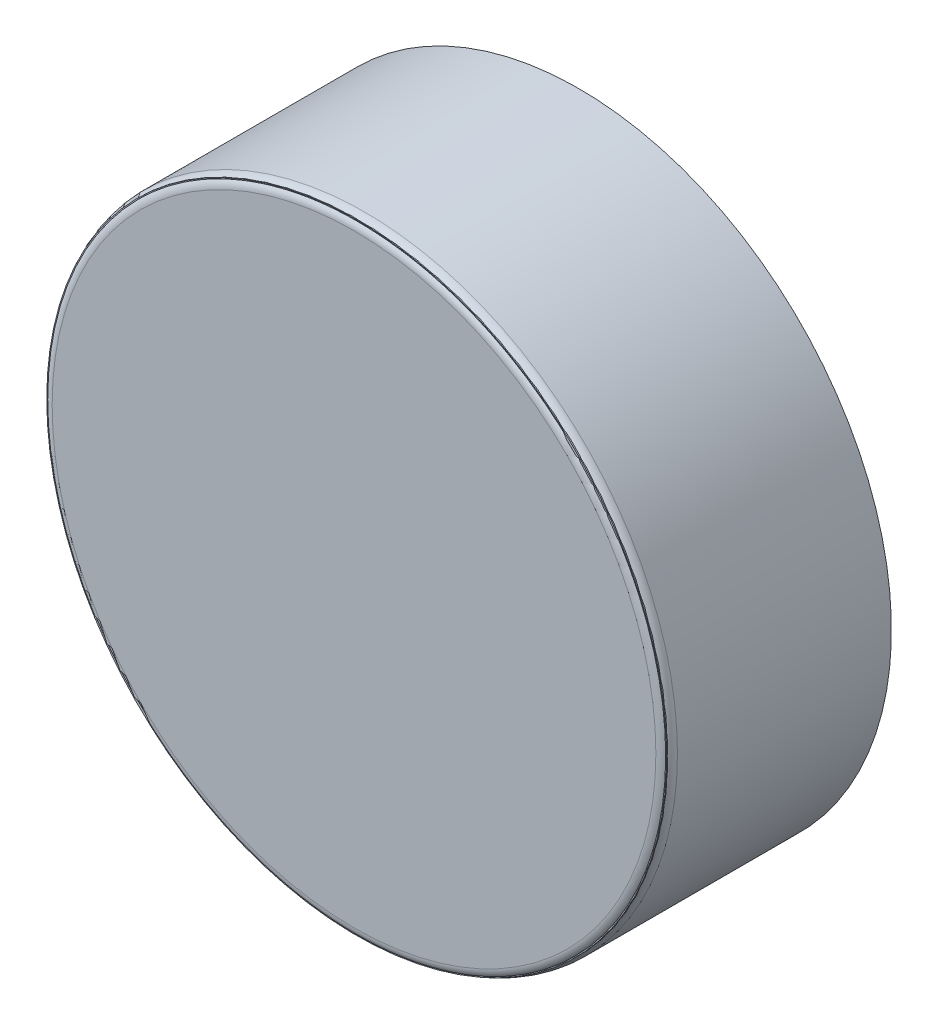
SolidWorks part; units mm, degrees
material "Rubber"
ref_plane "Front Plane" through (0, 0, 0) normal (0, 0, 1) x (1, 0, 0)
ref_plane "Top Plane" through (0, 0, 0) normal (0, 1, 0) x (1, 0, 0)
ref_plane "Right Plane" through (0, 0, 0) normal (1, 0, 0) x (0, 0, -1)
sketch "Sketch1" plane through (0, 0, 0) normal (0, 0, 1) x (1, 0, 0)
  circle A0 centre (0, 0) radius 73.66
  dimension "D1" = 147.32
extrude "Boss-Extrude1" add sketch "Sketch1" along normal blind 0.635
sketch "Sketch2" plane through (0, 0, 0) normal (0, 0, -1) x (-1, 0, 0)
  circle A1 centre (0, 0) radius 73.025
  circle A2 centre (0, 0) radius 73.66
  circle A3 centre (0, 0) radius 73.66
  dimension "D1" = 0
  dimension "D2" = 0.635
extrude "Boss-Extrude2" add sketch "Sketch2" along normal blind 52.324
fillet "Fillet1" radius 2.54 1 edges at (73.66, 0, 0.635)
